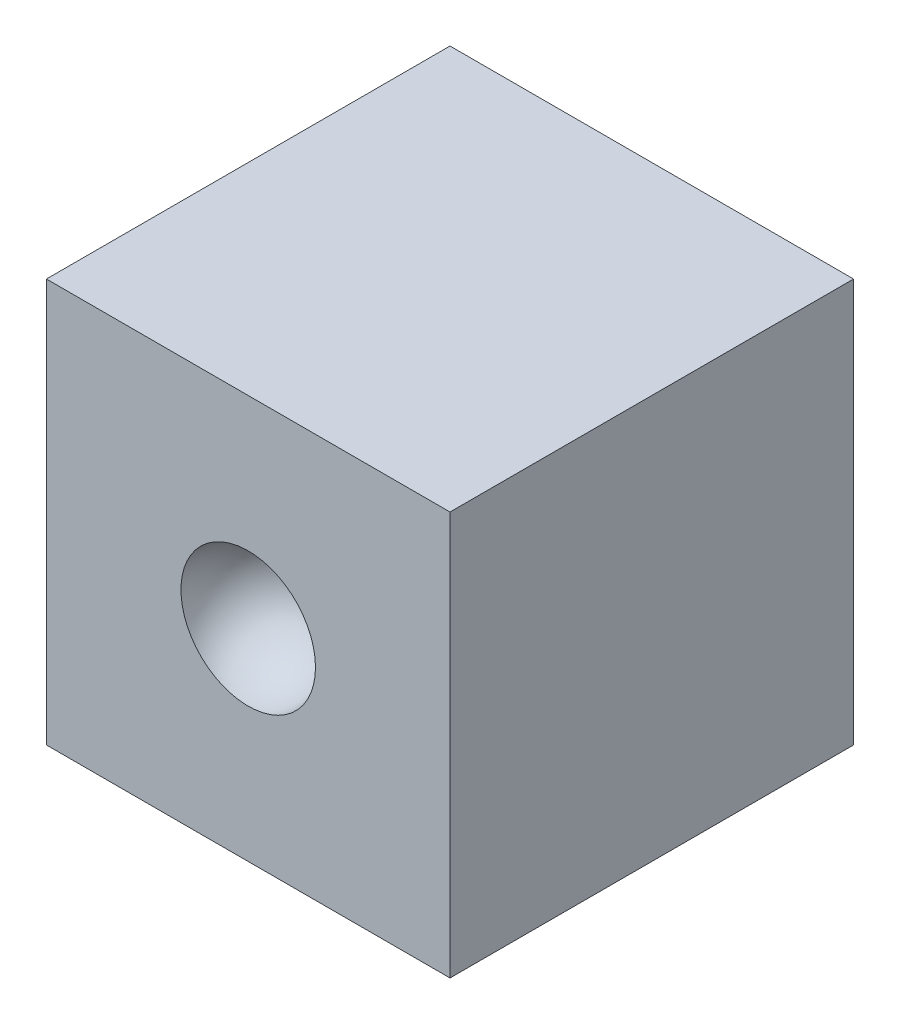
SolidWorks part; units mm, degrees
ref_plane "Front Plane" through (0, 0, 0) normal (0, 0, 1) x (1, 0, 0)
ref_plane "Top Plane" through (0, 0, 0) normal (0, 1, 0) x (1, 0, 0)
ref_plane "Right Plane" through (0, 0, 0) normal (1, 0, 0) x (0, 0, -1)
sketch "Sketch1" plane through (0, 0, 0) normal (0, 0, 1) x (1, 0, 0)
  line L1 (9, -9) -> (-9, -9)
  line L2 (9, -9) -> (9, 9)
  line L3 (9, 9) -> (-9, 9)
  line L4 (-9, -9) -> (-9, 9)
  line L5 (9, -9) -> (-9, 9) construction
  line L6 (9, 9) -> (-9, -9) construction
  point P0 (0, 0)
  dimension "D1" = 18
extrude "Boss-Extrude1" add sketch "Sketch1" along normal blind 18 contours L3 L4 L1 L2
sketch "Sketch2" plane through (0, 0, 18) normal (0, 0, 1) x (1, 0, 0)
  line L0 (0, 3) -> (0, -3)
  circle A0 centre (0, 0) radius 3
  dimension "D1" = 6
revolve "Cut-Revolve1" cut sketch "Sketch2" angle 360 about L0
